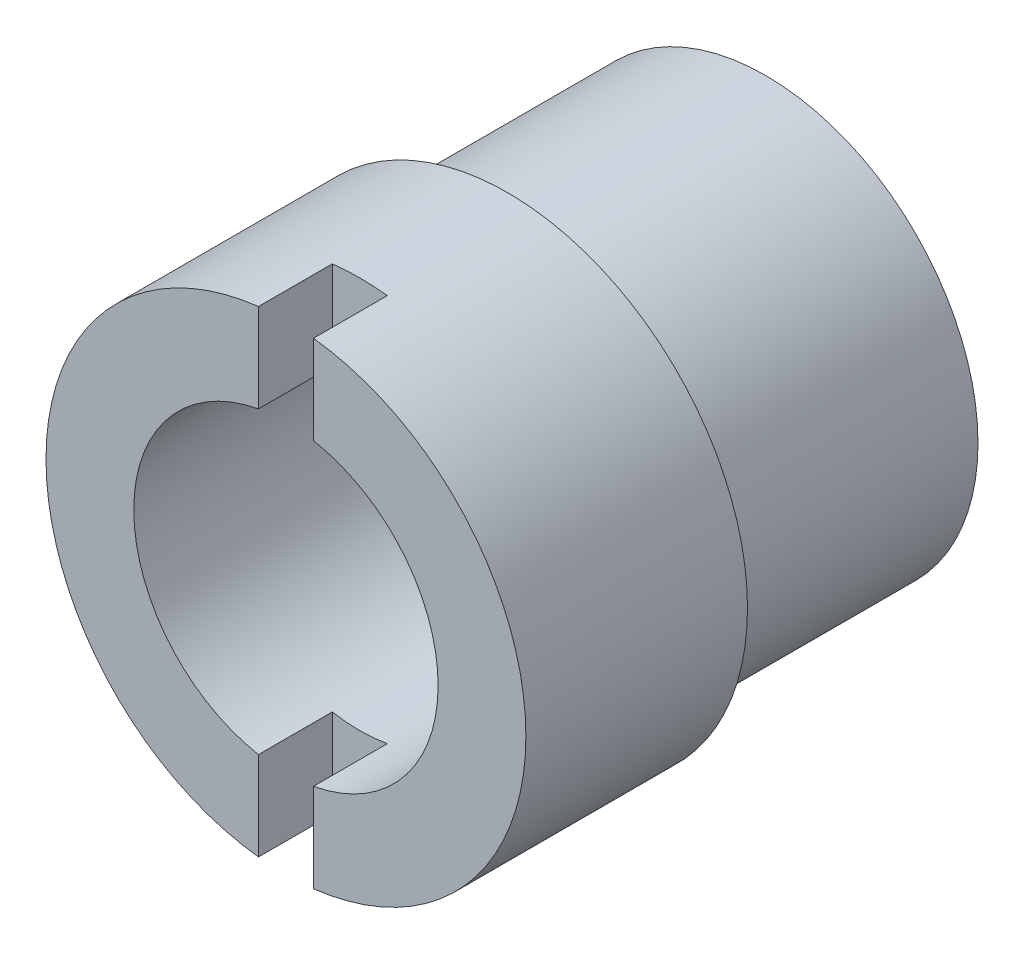
SolidWorks part; units mm, degrees
material "Chrome Stainless Steel"
ref_plane "Front Plane" through (0, 0, 0) normal (0, 0, 1) x (1, 0, 0)
ref_plane "Top Plane" through (0, 0, 0) normal (0, 1, 0) x (1, 0, 0)
ref_plane "Right Plane" through (0, 0, 0) normal (1, 0, 0) x (0, 0, -1)
sketch "Sketch1" plane through (0, 0, 0) normal (0, 0, 1) x (1, 0, 0)
  circle A0 centre (0, 0) radius 6.5405
  circle A1 centre (0, 0) radius 10.3124
  dimension "D1" = 13.081
  dimension "D2" = 20.6248
extrude "Boss-Extrude1" add sketch "Sketch1" along normal blind 9.525
cosmetic thread "Cosmetic Thread1" parameters "D1"=9.525, "D2"=19.304
sketch "Sketch2" plane through (0, 0, 0) normal (0, 0, -1) x (-1, 0, 0)
  circle A0 centre (0, 0) radius 6.5405 construction
  circle A1 centre (0, 0) radius 10.3124
  circle A2 centre (0, 0) radius 10.3124
  circle A3 centre (0, 0) radius 6.5405
  circle A4 centre (0, 0) radius 9.1186
  circle M5 centre (0, 0) radius 6.5405
  dimension "D2" = 18.2372
  dimension "D1" = 0
extrude "Boss-Extrude2" add sketch "Sketch2" along normal blind 11.0998 contours A4 M5
sketch "Sketch3" plane through (0, 0, 0) normal (0, 1, 0) x (1, 0, 0)
  line L0 (-10.3124, -9.525) -> (10.3124, -9.525) construction
  line L1 (-1.1811, -9.525) -> (1.1811, -9.525)
  line L2 (-1.1811, -9.525) -> (-1.1811, -6.35)
  line L3 (-1.1811, -6.35) -> (1.1811, -6.35)
  line L4 (1.1811, -9.525) -> (1.1811, -6.35)
  point P7 (-21.0146, -8.9631)
  point P8 (0, -6.35)
  dimension "D1" = 2.3622
  dimension "D2" = 3.175
extrude "Cut-Extrude1" cut sketch "Sketch3" against normal through all both and the other way through all
